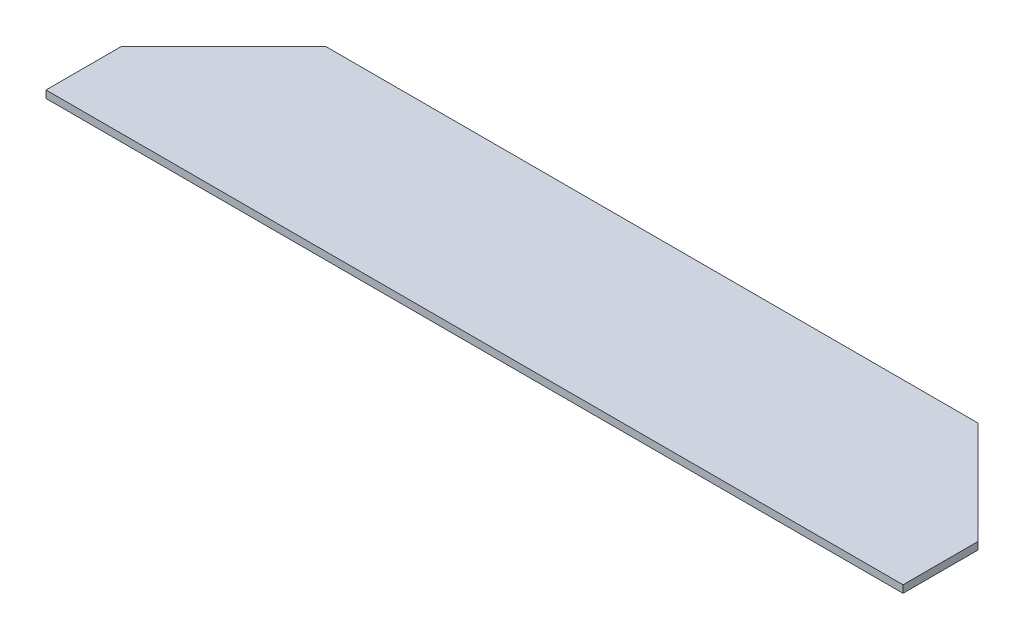
SolidWorks part; units mm, degrees
ref_plane "Front Plane" through (0, 0, 0) normal (0, 0, 1) x (1, 0, 0)
ref_plane "Top Plane" through (0, 0, 0) normal (0, 1, 0) x (1, 0, 0)
ref_plane "Right Plane" through (0, 0, 0) normal (1, 0, 0) x (0, 0, -1)
sketch "Sketch1" plane through (0, 0, 0) normal (0, 1, 0) x (1, 0, 0)
  line L1 (685.8, 142.0622) -> (-685.8, 142.0622)
  line L2 (685.8, 142.0622) -> (685.8, -142.0622)
  line L3 (685.8, -142.0622) -> (-685.8, -142.0622)
  line L4 (-685.8, 142.0622) -> (-685.8, -142.0622)
  line L5 (0, -142.0622) -> (0, 142.0622) construction
  line L6 (685.8, 0) -> (-685.8, 0) construction
  point P0 (0, 0)
  dimension "D1" = 1371.6
  dimension "D2" = 284.1244
extrude "Boss-Extrude1" add sketch "Sketch1" along normal blind 11.8872
sketch "Sketch3" plane through (0, 11.8872, 0) normal (0, 1, 0) x (1, 0, 0)
  line L0 (-685.8, -22.0622) -> (-521.6756, 142.0622)
  line L1 (-685.8, 142.0622) -> (-685.8, -142.0622) construction
  line L2 (-685.8, -142.0622) -> (685.8, -142.0622) construction
  line L3 (-521.6756, 142.0622) -> (-685.8, 142.0622)
  line L4 (-685.8, 142.0622) -> (-685.8, -22.0622)
  line L5 (685.8, 142.0622) -> (-685.8, 142.0622) construction
  line L6 (0, 142.0622) -> (0, -142.0622) construction
  line L7 (685.8, 142.0622) -> (685.8, -22.0622)
  line L8 (521.6756, 142.0622) -> (685.8, 142.0622)
  line L9 (685.8, -22.0622) -> (521.6756, 142.0622)
  point P14 (-566.4562, 136.525)
  dimension "D1" = 120
  dimension "D2" = 45
extrude "Cut-Extrude1" cut sketch "Sketch3" against normal through all
